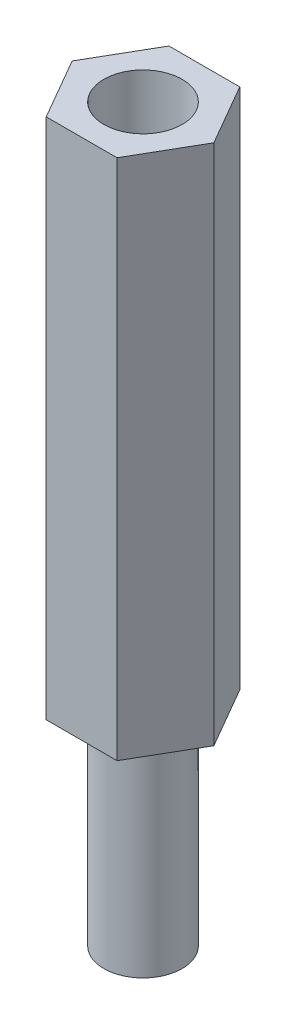
SolidWorks part; units mm, degrees
material "黄铜"
ref_plane "前视基准面" through (0, 0, 0) normal (0, 0, 1) x (1, 0, 0)
ref_plane "上视基准面" through (0, 0, 0) normal (0, 1, 0) x (1, 0, 0)
ref_plane "右视基准面" through (0, 0, 0) normal (1, 0, 0) x (0, 0, -1)
sketch "草图1" plane through (0, 0, 0) normal (0, 1, 0) x (1, 0, 0)
  line L1 (2.7135, 0) -> (1.3568, 2.35)
  line L2 (1.3568, 2.35) -> (-1.3568, 2.35)
  line L3 (-1.3568, 2.35) -> (-2.7135, 0)
  line L4 (-2.7135, 0) -> (-1.3568, -2.35)
  line L5 (-1.3568, -2.35) -> (1.3568, -2.35)
  line L6 (1.3568, -2.35) -> (2.7135, 0)
  circle A0 centre (0, 0) radius 1.5
  circle A1 centre (0, 0) radius 2.35 construction
  dimension "D1" = 3
  dimension "D2" = 4.7
extrude "凸台-拉伸1" add sketch "草图1" along normal blind 20
sketch "草图2" plane through (0, 0, 0) normal (0, -1, 0) x (-1, 0, 0)
  circle A0 centre (0, 0) radius 1.5
extrude "凸台-拉伸2" add sketch "草图2" along normal blind 8 separate body
